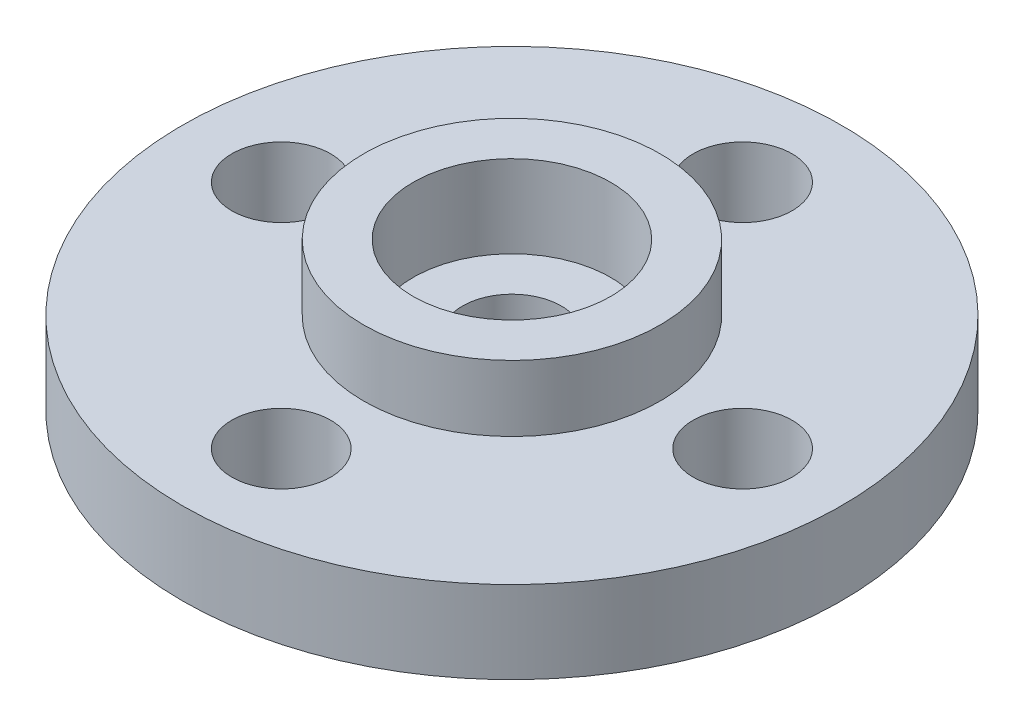
SolidWorks part; units mm, degrees
material "AISI 304"
ref_plane "前视基准面" through (0, 0, 0) normal (0, 0, 1) x (1, 0, 0)
ref_plane "上视基准面" through (0, 0, 0) normal (0, 1, 0) x (1, 0, 0)
ref_plane "右视基准面" through (0, 0, 0) normal (1, 0, 0) x (0, 0, -1)
sketch "草图1" plane through (0, 0, 0) normal (0, 1, 0) x (1, 0, 0)
  line L0 (0, 15.8996) -> (0, -14.3213) construction
  circle A0 centre (0, 0) radius 10
  circle A1 centre (0, 0) radius 1.5
  circle A2 centre (0, 7) radius 1.5
  circle A3 centre (7, 0) radius 1.5
  circle A4 centre (0, -7) radius 1.5
  circle A5 centre (-7, 0) radius 1.5
  dimension "D1" = 20
  dimension "D2" = 3
  dimension "D3" = 7
  dimension "D4" = 3
  dimension "D5" = 4
extrude "凸台-拉伸1" add sketch "草图1" along normal blind 2.5
sketch "草图2" plane through (0, 2.5, 0) normal (0, 1, 0) x (1, 0, 0)
  circle A0 centre (0, 0) radius 4.5
  circle A1 centre (0, 0) radius 3
  dimension "D1" = 9
  dimension "D2" = 6
extrude "凸台-拉伸2" add sketch "草图2" along normal blind 2
sketch "草图3" plane through (0, 2.5, 0) normal (0, 1, 0) x (1, 0, 0)
  circle A0 centre (0, 0) radius 3
  dimension "D1" = 6
extrude "切除-拉伸1" cut sketch "草图3" against normal blind 0.5
